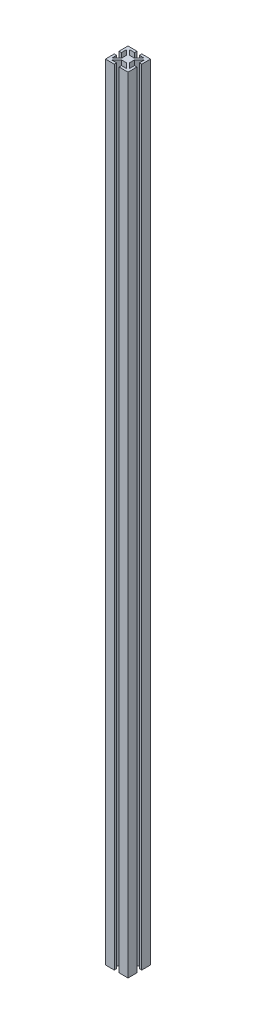
SolidWorks part; units mm, degrees
ref_plane "Front Plane" through (0, 0, 0) normal (0, 0, 1) x (1, 0, 0)
ref_plane "Top Plane" through (0, 0, 0) normal (0, 1, 0) x (1, 0, 0)
ref_plane "Right Plane" through (0, 0, 0) normal (1, 0, 0) x (0, 0, -1)
sketch "Sketch2" plane through (0.5947, 0, 0.5947) normal (0, 1, 0) x (1, 0, 0)
  line L0 (-0.5947, 0.5947) -> (-0.5947, 20.2394) construction
  line L1 (-0.5947, 0.5947) -> (-20.2394, 0.5947) construction
  line L2 (-0.5947, 0.5947) -> (-20.2394, 20.2394) construction
  line L3 (-19.6447, 19.6447) -> (-4.6587, 19.6447)
  line L4 (-4.6587, 19.6447) -> (-4.6587, 15.5807)
  line L5 (-4.6587, 15.5807) -> (-12.707, 15.5807)
  line L6 (-12.707, 15.5807) -> (-4.4774, 7.3511)
  line L7 (-4.4774, 7.3511) -> (3.288, 7.3511)
  line L8 (-19.6447, 19.6447) -> (-19.6447, 4.6587)
  line L9 (-19.6447, 4.6587) -> (-15.5807, 4.6587)
  line L10 (-15.5807, 4.6587) -> (-15.5807, 12.707)
  line L11 (-15.5807, 12.707) -> (-7.3511, 4.4774)
  line L12 (-7.3511, 4.4774) -> (-7.3511, -3.288)
  line L13 (-4.4774, -6.1617) -> (3.288, -6.1617)
  line L14 (-12.707, -14.3913) -> (-4.4774, -6.1617)
  line L15 (-4.6587, -14.3913) -> (-12.707, -14.3913)
  line L16 (-4.6587, -18.4553) -> (-4.6587, -14.3913)
  line L17 (-19.6447, -18.4553) -> (-4.6587, -18.4553)
  line L18 (-19.6447, -18.4553) -> (-19.6447, -3.4693)
  line L19 (-19.6447, -3.4693) -> (-15.5807, -3.4693)
  line L20 (-15.5807, -3.4693) -> (-15.5807, -11.5176)
  line L21 (-15.5807, -11.5176) -> (-7.3511, -3.288)
  line L22 (11.5176, 15.5807) -> (3.288, 7.3511)
  line L23 (3.4693, 15.5807) -> (11.5176, 15.5807)
  line L24 (3.4693, 19.6447) -> (3.4693, 15.5807)
  line L25 (18.4553, 19.6447) -> (3.4693, 19.6447)
  line L26 (18.4553, 19.6447) -> (18.4553, 4.6587)
  line L27 (18.4553, 4.6587) -> (14.3913, 4.6587)
  line L28 (14.3913, 4.6587) -> (14.3913, 12.707)
  line L29 (14.3913, 12.707) -> (6.1617, 4.4774)
  line L30 (6.1617, 4.4774) -> (6.1617, -3.288)
  line L31 (14.3913, -11.5176) -> (6.1617, -3.288)
  line L32 (14.3913, -3.4693) -> (14.3913, -11.5176)
  line L33 (18.4553, -3.4693) -> (14.3913, -3.4693)
  line L34 (18.4553, -18.4553) -> (18.4553, -3.4693)
  line L35 (18.4553, -18.4553) -> (3.4693, -18.4553)
  line L36 (3.4693, -18.4553) -> (3.4693, -14.3913)
  line L37 (3.4693, -14.3913) -> (11.5176, -14.3913)
  line L38 (11.5176, -14.3913) -> (3.288, -6.1617)
  point P26 (-7.3511, 0.5947)
  point P27 (-0.5947, 7.3511)
  point P44 (-0.5947, -6.1617)
  dimension "D1" = 38.1
  dimension "D2" = 8.128
  dimension "D3" = 13.5128
  dimension "D4" = 4.064
  dimension "D5" = 4.064
extrude "Boss-Extrude1" add sketch "Sketch2" along normal blind 1320.8
other "1515<1>"
